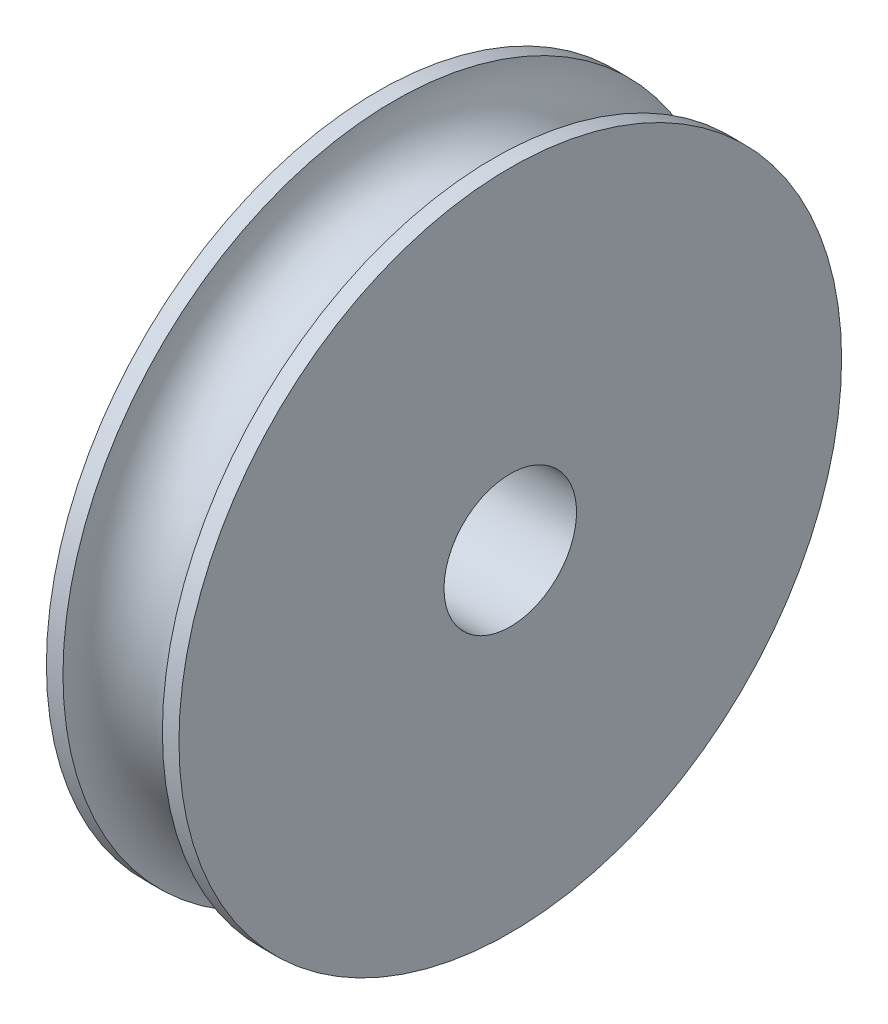
SolidWorks part; units mm, degrees
ref_plane "Front Plane" through (0, 0, 0) normal (0, 0, 1) x (1, 0, 0)
ref_plane "Top Plane" through (0, 0, 0) normal (0, 1, 0) x (1, 0, 0)
ref_plane "Right Plane" through (0, 0, 0) normal (1, 0, 0) x (0, 0, -1)
sketch "Sketch1" plane through (0, 0, 0) normal (0, 0, 1) x (1, 0, 0)
  line L0 (0, 0) -> (0, 20)
  line L1 (0, 20) -> (1, 20)
  line L3 (0, 0) -> (8, 0)
  line L5 (8, 20) -> (7, 20)
  line L6 (8, 0) -> (8, 20)
  arc A0 (1, 20) -> (7, 20) centre (4, 20) ccw
  dimension "D1" = 3
  dimension "D2" = 20
  dimension "D3" = 1
revolve "Revolve1" add sketch "Sketch1" angle 360 about L3
sketch "Sketch2" plane through (0, 0, 0) normal (-1, 0, 0) x (0, 0, 1)
  circle A0 centre (0, 0) radius 4
  dimension "D1" = 8
extrude "Cut-Extrude1" cut sketch "Sketch2" against normal blind 10
